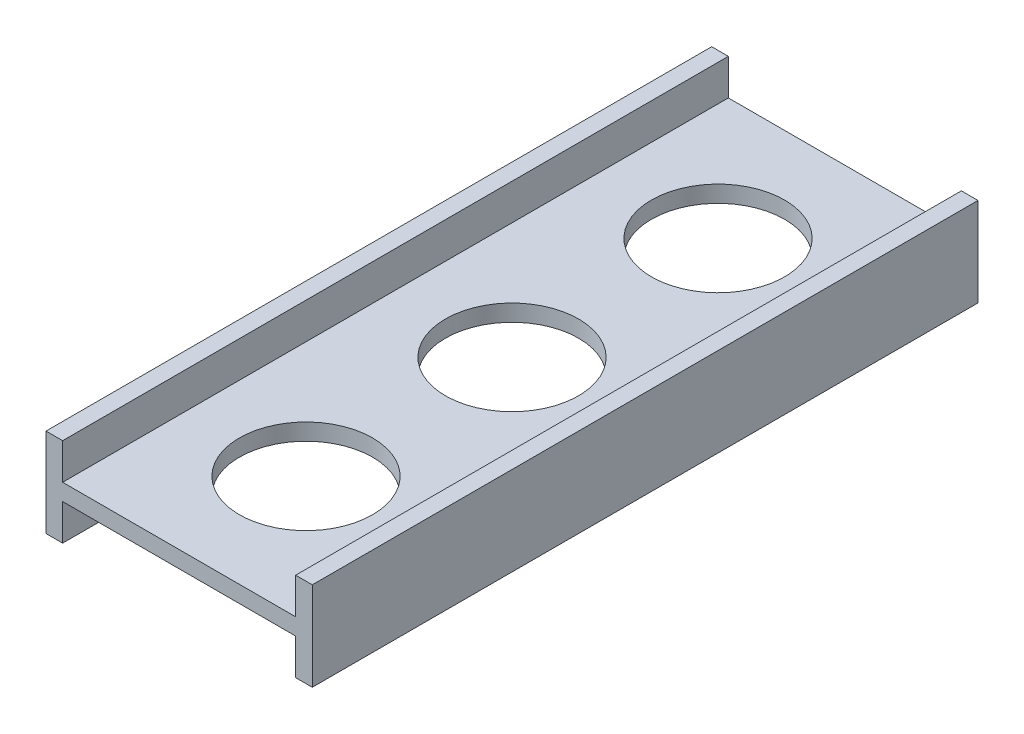
SolidWorks part; units mm, degrees
ref_plane "Front Plane" through (0, 0, 0) normal (0, 0, 1) x (1, 0, 0)
ref_plane "Top Plane" through (0, 0, 0) normal (0, 1, 0) x (1, 0, 0)
ref_plane "Right Plane" through (0, 0, 0) normal (1, 0, 0) x (0, 0, -1)
sketch "Sketch1" plane through (0, 0, 0) normal (0, 0, 1) x (1, 0, 0)
  line L0 (0, 0) -> (9.525, 0)
  line L1 (9.525, 0) -> (9.525, 20.6248)
  line L2 (9.525, 20.6248) -> (142.875, 20.6248)
  line L3 (142.875, 20.6248) -> (142.875, 0)
  line L4 (142.875, 0) -> (152.4, 0)
  line L5 (152.4, 0) -> (152.4, 50.8)
  line L6 (152.4, 50.8) -> (142.875, 50.8)
  line L7 (142.875, 50.8) -> (142.875, 30.1752)
  line L8 (142.875, 30.1752) -> (9.525, 30.1752)
  line L9 (9.525, 30.1752) -> (9.525, 50.8)
  line L10 (9.525, 50.8) -> (0, 50.8)
  line L11 (0, 50.8) -> (0, 0)
  line L12 (0, 25.4) -> (152.4, 25.4) construction
  dimension "D1" = 9.525
  dimension "D2" = 9.525
  dimension "D3" = 152.4
  dimension "D4" = 50.8
  dimension "D5" = 4.7752
  dimension "D6" = 4.7752
  dimension "D7" = 9.525
  dimension "D8" = 9.525
extrude "Boss-Extrude1" add sketch "Sketch1" against normal blind 381
ref_plane "Plane1" through (0, 30.1752, 0) normal (0, 1, 0) x (-1, 0, 0)
sketch "Sketch2" plane through (0, 30.1752, 0) normal (0, 1, 0) x (-1, 0, 0)
  line L0 (-76.2, 0) -> (-76.2, -381) construction
  line L1 (-142.875, 0) -> (-9.525, 0) construction
  line L2 (-142.875, -381) -> (-9.525, -381) construction
  line L3 (-76.2, -190.5) -> (-20.5921, -190.5) construction
  line L4 (-76.2, -190.5) -> (-20.5921, -190.5) construction
  circle A0 centre (-76.2, -308.4081) radius 38.1
  circle A1 centre (-76.2, -190.5) radius 38.1
  circle A2 centre (-76.2, -72.5919) radius 38.1
  dimension "D2" = 190.5
extrude "Cut-Extrude1" cut sketch "Sketch2" against normal blind 889
